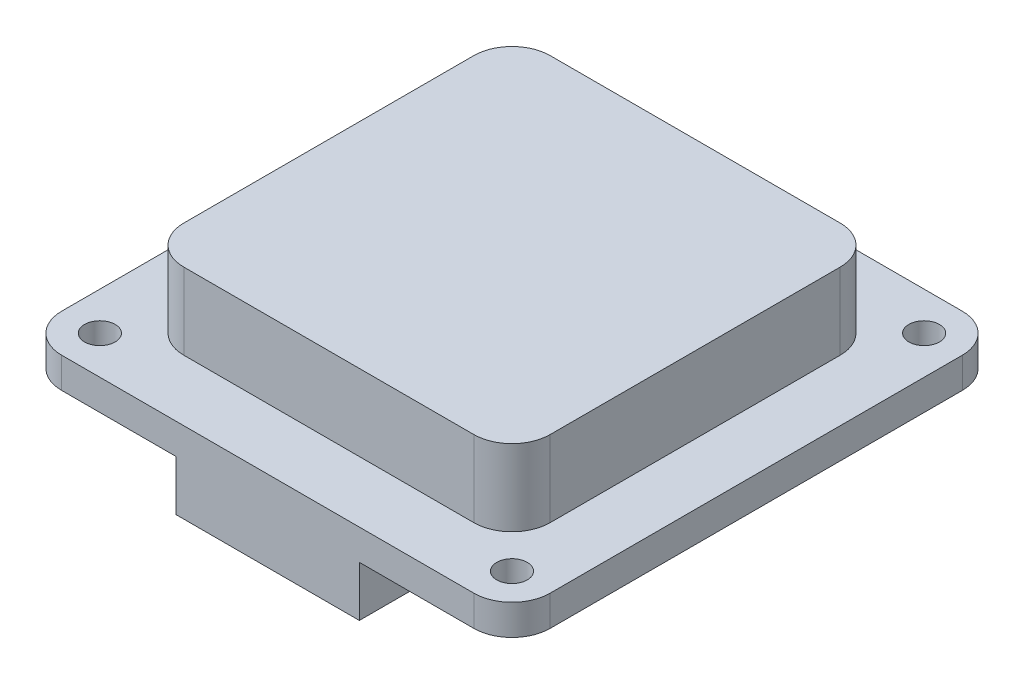
SolidWorks part; units mm, degrees
ref_plane "Front Plane" through (0, 0, 0) normal (0, 0, 1) x (1, 0, 0)
ref_plane "Top Plane" through (0, 0, 0) normal (0, 1, 0) x (1, 0, 0)
ref_plane "Right Plane" through (0, 0, 0) normal (1, 0, 0) x (0, 0, -1)
sketch "Sketch1" plane through (0, 0, 0) normal (0, 1, 0) x (1, 0, 0)
  line L1 (-13.5, 16) -> (13.5, 16)
  line L2 (-16, 13.5) -> (-16, -13.5)
  line L3 (-13.5, -16) -> (13.5, -16)
  line L4 (16, 13.5) -> (16, -13.5)
  line L5 (-16, 16) -> (16, -16) construction
  line L6 (-16, -16) -> (16, 16) construction
  arc A0 (16, -13.5) -> (13.5, -16) centre (13.5, -13.5) cw
  arc A1 (16, 13.5) -> (13.5, 16) centre (13.5, 13.5) ccw
  arc A2 (-13.5, 16) -> (-16, 13.5) centre (-13.5, 13.5) ccw
  arc A3 (-16, -13.5) -> (-13.5, -16) centre (-13.5, -13.5) ccw
  point P0 (0, 0)
  dimension "D3" = 2.5
  dimension "D1" = 32
  dimension "D2" = 32
extrude "Boss-Extrude1" add sketch "Sketch1" along normal blind 10.3
sketch "Sketch2" plane through (0, 10.3, 0) normal (0, 1, 0) x (1, 0, 0)
  line L0 (-16, 13.5) -> (-16, -13.5) construction
  line L1 (-9.5, -12) -> (9.5, -12)
  line L2 (-12, -9.5) -> (-12, 9.5)
  line L3 (-9.5, 12) -> (9.5, 12)
  line L4 (12, -9.5) -> (12, 9.5)
  line L5 (-12, -12) -> (12, 12) construction
  line L6 (-12, 12) -> (12, -12) construction
  line L7 (-13.5, -16) -> (13.5, -16) construction
  arc A0 (12, -9.5) -> (9.5, -12) centre (9.5, -9.5) cw
  arc A1 (12, 9.5) -> (9.5, 12) centre (9.5, 9.5) ccw
  arc A2 (-9.5, 12) -> (-12, 9.5) centre (-9.5, 9.5) ccw
  arc A3 (-12, -9.5) -> (-9.5, -12) centre (-9.5, -9.5) ccw
  point P0 (0, 0)
  dimension "D3" = 2.5
  dimension "D1" = 4
  dimension "D2" = 4
extrude "Cut-Extrude1" cut sketch "Sketch2" against normal blind 5 flip side to cut
sketch "Sketch3" plane through (0, 10.3, 0) normal (0, 1, 0) x (1, 0, 0)
  text T0 "<b>TAOGLAS</b>" font "Century Gothic" height 3.5
sketch "Sketch4" plane through (0, 5.3, 0) normal (0, 1, 0) x (1, 0, 0)
  circle A2 centre (-13.5, 13.5) radius 1
  circle A3 centre (13.5, -13.5) radius 1
  circle A5 centre (-13.5, -13.5) radius 1
  circle A6 centre (13.5, 13.5) radius 1
extrude "Cut-Extrude2" cut sketch "Sketch4" against normal through all both and the other way through all
sketch "Sketch5" plane through (0, 0, 16) normal (0, 0, 1) x (1, 0, 0)
  line L0 (-17.2443, 3.3) -> (-17.2443, -0.6146)
  line L4 (6, 3.3) -> (6, 0.3)
  line L5 (-6, 3.3) -> (-6, 0.3)
  line L6 (-6, 0.3) -> (-6, 0)
  line L7 (-13.5, 0) -> (13.5, 0) construction
  line L9 (6, 0) -> (6, 0.3)
  line L12 (-17.2443, -0.6146) -> (-6, -0.6146)
  line L13 (-6, -0.6146) -> (-6, 0)
  line L14 (-17.2443, 3.3) -> (-6, 3.3)
  line L15 (6, 3.3) -> (18.6559, 3.3)
  line L16 (18.6559, 3.3) -> (18.6559, -0.6146)
  line L17 (18.6559, -0.6146) -> (6, -0.6146)
  line L18 (6, -0.6146) -> (6, 0)
extrude "Cut-Extrude3" cut sketch "Sketch5" against normal through all both and the other way through all
sketch "Sketch6" plane through (0, 0, 0) normal (0, -1, 0) x (1, 0, 0)
  line L3 (-6, 11) -> (6, 11)
  line L5 (6, 16) -> (6, -16) construction
  line L7 (-6, 11) -> (-6, -11)
  line L9 (-6, -11) -> (6, -11)
  line L12 (6, 11) -> (6, -11)
extrude "Cut-Extrude4" cut sketch "Sketch6" against normal up to surface (3.3 mm away) up to face at (-13.5, 3.3, 14.5)
